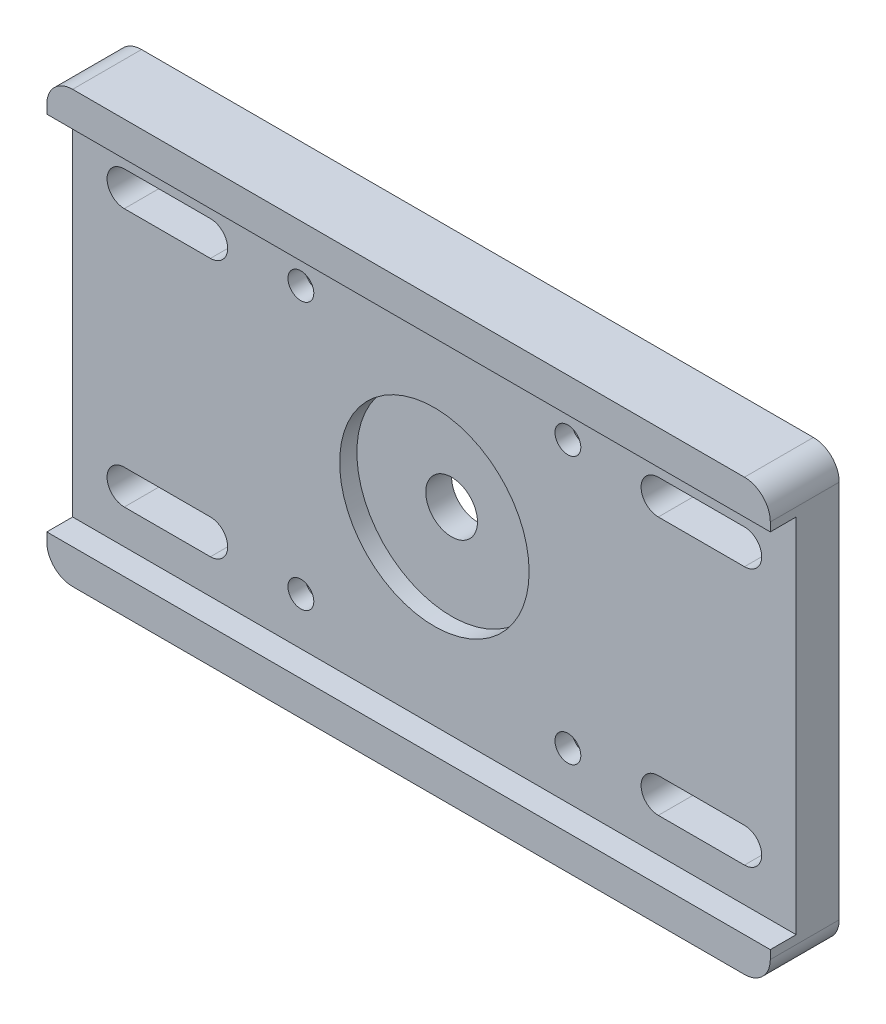
SolidWorks part; units mm, degrees
ref_plane "Alzado" through (0, 0, 0) normal (0, 0, 1) x (1, 0, 0)
ref_plane "Planta" through (0, 0, 0) normal (0, 1, 0) x (1, 0, 0)
ref_plane "Vista lateral" through (0, 0, 0) normal (1, 0, 0) x (0, 0, -1)
sketch "Croquis1" plane through (0, 0, 0) normal (0, 0, 1) x (1, 0, 0)
  line L1 (-42, 25) -> (42, 25)
  line L2 (-42, 25) -> (-42, -25)
  line L3 (-42, -25) -> (42, -25)
  line L4 (42, 25) -> (42, -25)
  line L5 (-42, 25) -> (42, -25) construction
  line L6 (-42, -25) -> (42, 25) construction
  point P0 (0, 0)
  dimension "D1" = 50
  dimension "D2" = 84
extrude "Saliente-Extruir1" add sketch "Croquis1" along normal blind 5
sketch "Croquis6" plane through (0, 0, 5) normal (0, 0, 1) x (1, 0, 0)
  line L0 (-36, 15) -> (-26, 15) construction
  line L1 (-31, 15) -> (31, 15) construction
  line L2 (-31, 15) -> (-31, -15) construction
  line L3 (-31, -15) -> (31, -15) construction
  line L4 (31, 15) -> (31, -15) construction
  line L5 (-31, 15) -> (31, -15) construction
  line L6 (-31, -15) -> (31, 15) construction
  line L7 (-36, 17) -> (-26, 17)
  line L8 (-36, 13) -> (-26, 13)
  line L9 (36, 15) -> (26, 15) construction
  line L10 (36, 13) -> (26, 13)
  line L11 (36, 17) -> (26, 17)
  line L12 (36, -15) -> (26, -15) construction
  line L13 (36, -17) -> (26, -17)
  line L14 (36, -13) -> (26, -13)
  line L15 (-36, -15) -> (-26, -15) construction
  line L16 (-36, -13) -> (-26, -13)
  line L17 (-36, -17) -> (-26, -17)
  arc A0 (-36, 17) -> (-36, 13) centre (-36, 15) ccw
  arc A1 (-26, 13) -> (-26, 17) centre (-26, 15) ccw
  arc A2 (36, 13) -> (36, 17) centre (36, 15) ccw
  arc A3 (26, 17) -> (26, 13) centre (26, 15) ccw
  arc A4 (36, -17) -> (36, -13) centre (36, -15) ccw
  arc A5 (26, -13) -> (26, -17) centre (26, -15) ccw
  arc A6 (-36, -13) -> (-36, -17) centre (-36, -15) ccw
  arc A7 (-26, -17) -> (-26, -13) centre (-26, -15) ccw
  point P0 (0, 0)
  point P8 (-31, 15)
  point P14 (31, 15)
  point P21 (31, -15)
  point P28 (-31, -15)
  dimension "D7" = 2
  dimension "D8" = 2
  dimension "D9" = 2
  dimension "D10" = 2
  dimension "D1" = 30
  dimension "D2" = 62
  dimension "D3" = 10
  dimension "D4" = 10
  dimension "D5" = 10
  dimension "D6" = 10
extrude "Cortar-Extruir5" cut sketch "Croquis6" against normal through all
sketch "Croquis8" plane through (0, 0, 5) normal (0, 0, 1) x (1, 0, 0)
  line L0 (-31, 17) -> (-31, -17) construction
  line L1 (-26, 17) -> (-36, 17) construction
  line L2 (-36, -17) -> (-26, -17) construction
  line L3 (31, 17) -> (31, -17) construction
  line L4 (36, 17) -> (26, 17) construction
  line L5 (26, -17) -> (36, -17) construction
  line L6 (-38, -15) -> (38, -15) construction
  line L7 (-38, 15) -> (38, 15) construction
  line L9 (-21, 21) -> (21, 21) construction
  line L10 (-21, 21) -> (-21, -21) construction
  line L11 (-21, -21) -> (21, -21) construction
  line L12 (21, 21) -> (21, -21) construction
  line L13 (-21, 21) -> (21, -21) construction
  line L14 (-21, -21) -> (21, 21) construction
  arc A0 (-36, -13) -> (-36, -17) centre (-36, -15) ccw construction
  arc A1 (36, -17) -> (36, -13) centre (36, -15) ccw construction
  arc A2 (-36, 17) -> (-36, 13) centre (-36, 15) ccw construction
  arc A3 (36, 13) -> (36, 17) centre (36, 15) ccw construction
  point P28 (0, 0)
  dimension "D1" = 42
  dimension "D2" = 42
sketch "Croquis2" plane through (0, 0, 5) normal (0, 0, 1) x (1, 0, 0)
  circle A0 centre (0, 0) radius 3
  dimension "D1" = 6
extrude "Cortar-Extruir1" cut sketch "Croquis2" against normal through all
sketch "Croquis3" plane through (0, 0, 5) normal (0, 0, 1) x (1, 0, 0)
  circle A0 centre (0, 0) radius 11
  dimension "D1" = 22
extrude "Cortar-Extruir2" cut sketch "Croquis3" against normal blind 2
sketch "Croquis4" plane through (0, 0, 5) normal (0, 0, 1) x (1, 0, 0)
  line L1 (-15.5, 15.5) -> (15.5, 15.5) construction
  line L2 (-15.5, 15.5) -> (-15.5, -15.5) construction
  line L3 (-15.5, -15.5) -> (15.5, -15.5) construction
  line L4 (15.5, 15.5) -> (15.5, -15.5) construction
  line L5 (-15.5, 15.5) -> (15.5, -15.5) construction
  line L6 (-15.5, -15.5) -> (15.5, 15.5) construction
  circle A0 centre (15.5, 15.5) radius 1.5
  circle A1 centre (-15.5, 15.5) radius 1.5
  circle A2 centre (-15.5, -15.5) radius 1.5
  circle A3 centre (15.5, -15.5) radius 1.5
  point P0 (0, 0)
  dimension "D3" = 3
  dimension "D4" = 3
  dimension "D5" = 3
  dimension "D6" = 3
  dimension "D1" = 31
  dimension "D2" = 31
extrude "Cortar-Extruir3" cut sketch "Croquis4" against normal through all
sketch "Croquis5" plane through (0, 0, 0) normal (0, 0, -1) x (-1, 0, 0)
  circle A0 centre (-15.5, 15.5) radius 3.5
  circle A1 centre (15.5, 15.5) radius 3.5
  circle A2 centre (15.5, -15.5) radius 3.5
  circle A3 centre (-15.5, -15.5) radius 3.5
  dimension "D1" = 7
  dimension "D2" = 7
  dimension "D3" = 7
  dimension "D4" = 7
extrude "Cortar-Extruir4" cut sketch "Croquis5" against normal blind 3
sketch "Croquis7" plane through (0, 0, 5) normal (0, 0, 1) x (1, 0, 0)
  line L1 (-42, 25) -> (42, 25)
  line L2 (-42, 25) -> (-42, 21)
  line L3 (-42, 21) -> (42, 21)
  line L4 (42, 25) -> (42, 21)
  line L5 (42, -25) -> (42, 25) construction
  line L7 (-42, -25) -> (42, -25)
  line L8 (-42, -25) -> (-42, -21)
  line L9 (-42, -21) -> (42, -21)
  line L10 (42, -25) -> (42, -21)
  dimension "D1" = 4
  dimension "D2" = 84
  dimension "D3" = 4
  dimension "D4" = 84
extrude "Saliente-Extruir2" add sketch "Croquis7" along normal blind 3
fillet "Redondeo1" radius 3 4 edges at (42, -25, 4) (-42, -25, 4) (42, 25, 4) (-42, 25, 4)
chamfer "Chaflán1" distance 1 angle 45 16 edges at (31, 17, 0) (24, 15, 0) (38, 15, 0) (31, 13, 0) (31, -13, 0) (24, -15, 0) (38, -15, 0) (31, -17, 0) (-31, 17, 0) (-38, 15, 0) (-24, 15, 0) (-31, 13, 0) (-31, -13, 0) (-38, -15, 0) (-24, -15, 0) (-31, -17, 0)
